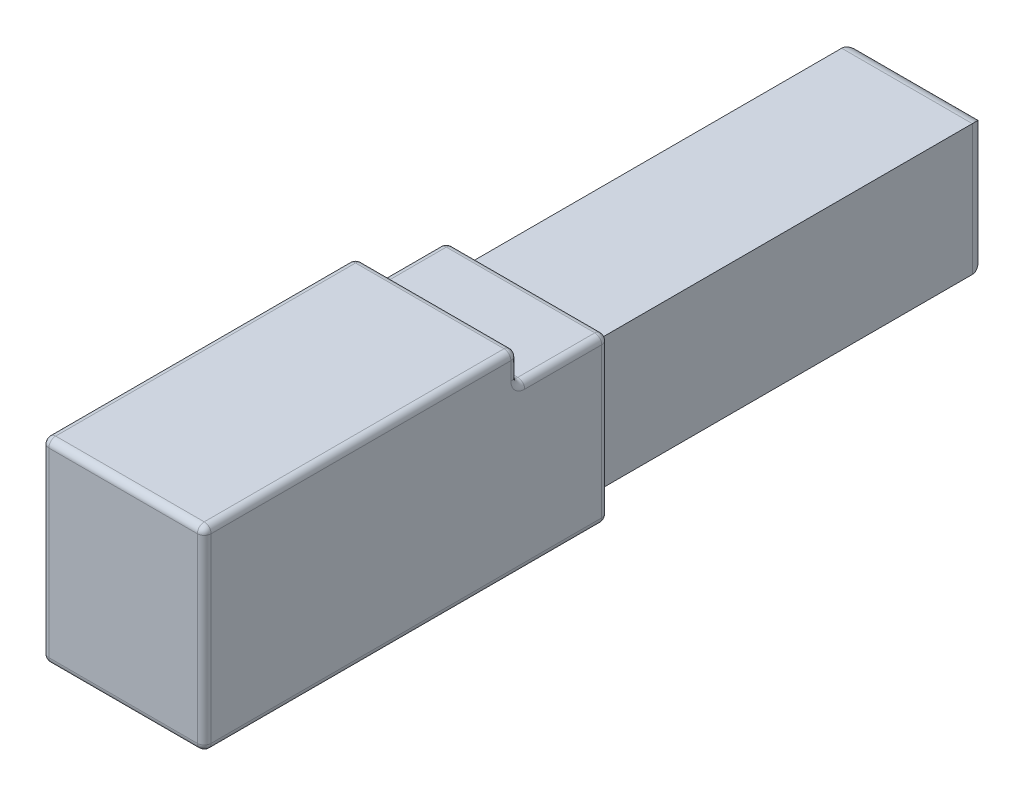
SolidWorks part; units mm, degrees
material "PE Low/Medium Density"
ref_plane "Front Plane" through (0, 0, 0) normal (0, 0, 1) x (1, 0, 0)
ref_plane "Top Plane" through (0, 0, 0) normal (0, 1, 0) x (1, 0, 0)
ref_plane "Right Plane" through (0, 0, 0) normal (1, 0, 0) x (0, 0, -1)
sketch "Sketch1" plane through (0, 0, 0) normal (1, 0, 0) x (0, 0, -1)
  line L0 (0, 0) -> (0, 18.034)
  line L1 (0, 18.034) -> (28.956, 18.034)
  line L2 (28.956, 18.034) -> (28.956, 15.113)
  line L3 (28.956, 15.113) -> (37.338, 15.113)
  line L4 (37.338, 15.113) -> (37.338, 0)
  line L9 (37.338, 0) -> (0, 0)
  dimension "D1" = 18.034
  dimension "D2" = 15.113
  dimension "D3" = 28.956
  dimension "D4" = 37.338
extrude "Boss-Extrude1" add sketch "Sketch1" along normal blind 14.986
sketch "Sketch2" plane through (0, 0, -37.338) normal (0, 0, -1) x (-1, 0, 0)
  line L0 (-14.986, 0) -> (0, 15.113) construction
  line L1 (-13.5255, 1.524) -> (-1.4605, 1.524)
  line L2 (-13.5255, 1.524) -> (-13.5255, 13.589)
  line L3 (-13.5255, 13.589) -> (-1.4605, 13.589)
  line L4 (-1.4605, 1.524) -> (-1.4605, 13.589)
  line L5 (-13.5255, 1.524) -> (-1.4605, 13.589) construction
  line L6 (-13.5255, 13.589) -> (-1.4605, 1.524) construction
  line L7 (-14.986, 15.113) -> (0, 0) construction
  point P0 (-7.493, 7.5565)
  dimension "D1" = 12.065
extrude "Boss-Extrude2" add sketch "Sketch2" along normal blind 36.322
fillet "Fillet1" radius 1.27 4 edges at (1.4605, 7.5565, -73.66) (7.493, 1.524, -73.66) (13.5255, 7.5565, -73.66) (7.493, 13.589, -73.66)
fillet "Fillet2" radius 0.635 18 edges at (7.493, 18.034, -28.956) (7.493, 18.034, 0) (7.493, 15.113, -37.338) (7.493, 0, 0) (7.493, 0, -37.338) (0, 7.5565, -37.338) (0, 15.113, -33.147) (0, 16.5735, -28.956) (0, 18.034, -14.478) (0, 9.017, 0) (0, 0, -18.669) (14.986, 9.017, 0) (14.986, 18.034, -14.478) (14.986, 16.5735, -28.956) (14.986, 15.113, -33.147) (14.986, 7.5565, -37.338) (14.986, 0, -18.669) (7.493, 15.113, -28.956)
sketch "Sketch3" plane through (0, 0, -73.66) normal (0, 0, -1) x (-1, 0, 0)
  line L0 (-2.7305, 2.794) -> (-12.2555, 12.319) construction
  line L1 (-12.2555, 2.794) -> (-2.7305, 12.319) construction
  circle A0 centre (-7.493, 7.5565) radius 4.445
  dimension "D1" = 8.89
extrude "Cut-Extrude1" cut sketch "Sketch3" against normal blind 31.75
